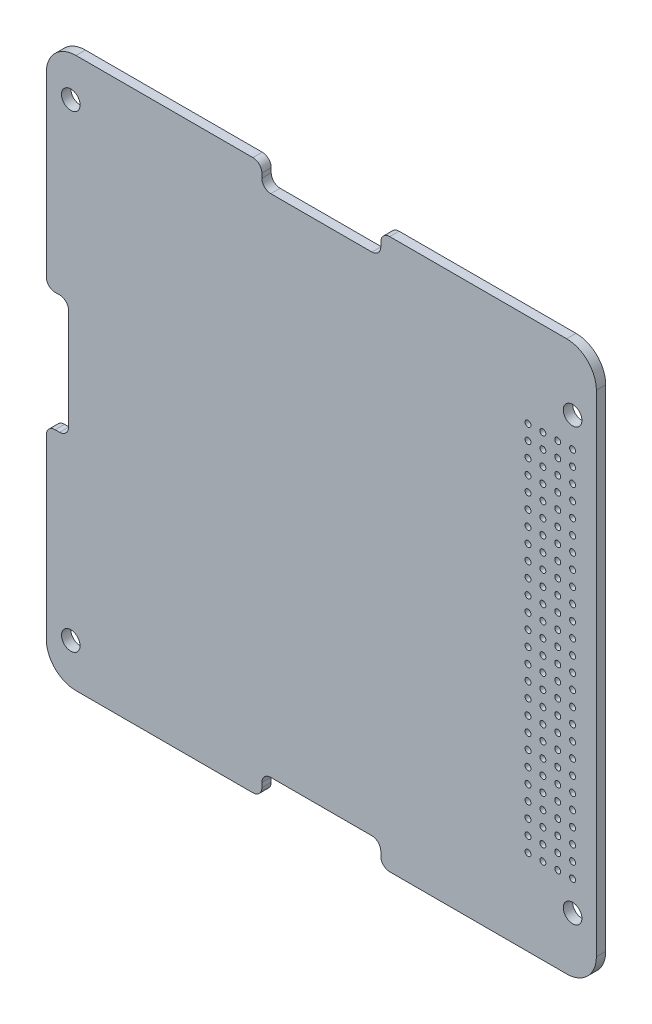
SolidWorks part; units mm, degrees
ref_plane "Front Plane" through (0, 0, 0) normal (0, 0, 1) x (1, 0, 0)
ref_plane "Top Plane" through (0, 0, 0) normal (0, 1, 0) x (1, 0, 0)
ref_plane "Right Plane" through (0, 0, 0) normal (1, 0, 0) x (0, 0, -1)
sketch "Sketch1" plane through (0, 0, 0) normal (0, 0, 1) x (1, 0, 0)
  line L0 (5.08, 0) -> (35.306, 0)
  line L1 (36.83, 1.524) -> (36.83, 2.286)
  line L2 (38.354, 3.81) -> (55.626, 3.81)
  line L3 (57.15, 2.286) -> (57.15, 1.524)
  line L4 (58.674, 0) -> (88.9, 0)
  line L5 (93.98, 5.08) -> (93.98, 88.9)
  line L6 (88.9, 93.98) -> (58.674, 93.98)
  line L7 (57.15, 92.456) -> (57.15, 91.694)
  line L8 (55.626, 90.17) -> (38.354, 90.17)
  line L9 (36.83, 91.694) -> (36.83, 92.456)
  line L10 (35.306, 93.98) -> (5.08, 93.98)
  line L11 (0, 88.9) -> (0, 58.674)
  line L12 (1.524, 57.15) -> (2.286, 57.15)
  line L13 (3.81, 55.626) -> (3.81, 38.354)
  line L14 (2.286, 36.83) -> (1.524, 36.83)
  line L15 (0, 35.306) -> (0, 5.08)
  arc A0 (5.08, 0) -> (0, 5.08) centre (5.08, 5.08) cw
  arc A1 (88.9, 0) -> (93.98, 5.08) centre (88.9, 5.08) ccw
  arc A2 (93.98, 88.9) -> (88.9, 93.98) centre (88.9, 88.9) ccw
  arc A3 (5.08, 93.98) -> (0, 88.9) centre (5.08, 88.9) ccw
  circle A4 centre (4.191, 86.995) radius 1.5875
  circle A5 centre (89.916, 83.185) radius 1.5875
  circle A6 centre (89.916, 9.525) radius 1.5875
  circle A7 centre (4.191, 6.985) radius 1.5875
  circle A8 centre (82.296, 78.105) radius 0.508
  circle A9 centre (84.836, 78.105) radius 0.508
  circle A10 centre (87.376, 78.105) radius 0.508
  circle A11 centre (89.916, 78.105) radius 0.508
  circle A12 centre (84.836, 75.565) radius 0.508
  circle A13 centre (87.376, 75.565) radius 0.508
  circle A14 centre (89.916, 75.565) radius 0.508
  circle A15 centre (84.836, 73.025) radius 0.508
  circle A16 centre (87.376, 73.025) radius 0.508
  circle A17 centre (89.916, 73.025) radius 0.508
  circle A18 centre (84.836, 70.485) radius 0.508
  circle A19 centre (87.376, 70.485) radius 0.508
  circle A20 centre (89.916, 70.485) radius 0.508
  circle A21 centre (84.836, 67.945) radius 0.508
  circle A22 centre (87.376, 67.945) radius 0.508
  circle A23 centre (89.916, 67.945) radius 0.508
  circle A24 centre (84.836, 65.405) radius 0.508
  circle A25 centre (87.376, 65.405) radius 0.508
  circle A26 centre (89.916, 65.405) radius 0.508
  circle A27 centre (84.836, 62.865) radius 0.508
  circle A28 centre (87.376, 62.865) radius 0.508
  circle A29 centre (89.916, 62.865) radius 0.508
  circle A30 centre (84.836, 60.325) radius 0.508
  circle A31 centre (87.376, 60.325) radius 0.508
  circle A32 centre (89.916, 60.325) radius 0.508
  circle A33 centre (84.836, 57.785) radius 0.508
  circle A34 centre (87.376, 57.785) radius 0.508
  circle A35 centre (89.916, 57.785) radius 0.508
  circle A36 centre (84.836, 55.245) radius 0.508
  circle A37 centre (87.376, 55.245) radius 0.508
  circle A38 centre (89.916, 55.245) radius 0.508
  circle A39 centre (84.836, 52.705) radius 0.508
  circle A40 centre (87.376, 52.705) radius 0.508
  circle A41 centre (89.916, 52.705) radius 0.508
  circle A42 centre (84.836, 50.165) radius 0.508
  circle A43 centre (87.376, 50.165) radius 0.508
  circle A44 centre (89.916, 50.165) radius 0.508
  circle A45 centre (84.836, 47.625) radius 0.508
  circle A46 centre (87.376, 47.625) radius 0.508
  circle A47 centre (89.916, 47.625) radius 0.508
  circle A48 centre (84.836, 45.085) radius 0.508
  circle A49 centre (87.376, 45.085) radius 0.508
  circle A50 centre (89.916, 45.085) radius 0.508
  circle A51 centre (84.836, 42.545) radius 0.508
  circle A52 centre (87.376, 42.545) radius 0.508
  circle A53 centre (89.916, 42.545) radius 0.508
  circle A54 centre (84.836, 40.005) radius 0.508
  circle A55 centre (87.376, 40.005) radius 0.508
  circle A56 centre (89.916, 40.005) radius 0.508
  circle A57 centre (84.836, 37.465) radius 0.508
  circle A58 centre (87.376, 37.465) radius 0.508
  circle A59 centre (89.916, 37.465) radius 0.508
  circle A60 centre (84.836, 34.925) radius 0.508
  circle A61 centre (87.376, 34.925) radius 0.508
  circle A62 centre (89.916, 34.925) radius 0.508
  circle A63 centre (84.836, 32.385) radius 0.508
  circle A64 centre (87.376, 32.385) radius 0.508
  circle A65 centre (89.916, 32.385) radius 0.508
  circle A66 centre (84.836, 29.845) radius 0.508
  circle A67 centre (87.376, 29.845) radius 0.508
  circle A68 centre (89.916, 29.845) radius 0.508
  circle A69 centre (84.836, 27.305) radius 0.508
  circle A70 centre (87.376, 27.305) radius 0.508
  circle A71 centre (89.916, 27.305) radius 0.508
  circle A72 centre (84.836, 24.765) radius 0.508
  circle A73 centre (87.376, 24.765) radius 0.508
  circle A74 centre (89.916, 24.765) radius 0.508
  circle A75 centre (84.836, 22.225) radius 0.508
  circle A76 centre (87.376, 22.225) radius 0.508
  circle A77 centre (89.916, 22.225) radius 0.508
  circle A78 centre (84.836, 19.685) radius 0.508
  circle A79 centre (87.376, 19.685) radius 0.508
  circle A80 centre (89.916, 19.685) radius 0.508
  circle A81 centre (84.836, 17.145) radius 0.508
  circle A82 centre (87.376, 17.145) radius 0.508
  circle A83 centre (89.916, 17.145) radius 0.508
  circle A84 centre (84.836, 14.605) radius 0.508
  circle A85 centre (87.376, 14.605) radius 0.508
  circle A86 centre (89.916, 14.605) radius 0.508
  circle A87 centre (82.296, 75.565) radius 0.508
  circle A88 centre (82.296, 73.025) radius 0.508
  circle A89 centre (82.296, 70.485) radius 0.508
  circle A90 centre (82.296, 67.945) radius 0.508
  circle A91 centre (82.296, 65.405) radius 0.508
  circle A92 centre (82.296, 62.865) radius 0.508
  circle A93 centre (82.296, 60.325) radius 0.508
  circle A94 centre (82.296, 57.785) radius 0.508
  circle A95 centre (82.296, 55.245) radius 0.508
  circle A96 centre (82.296, 52.705) radius 0.508
  circle A97 centre (82.296, 50.165) radius 0.508
  circle A98 centre (82.296, 47.625) radius 0.508
  circle A99 centre (82.296, 45.085) radius 0.508
  circle A100 centre (82.296, 42.545) radius 0.508
  circle A101 centre (82.296, 40.005) radius 0.508
  circle A102 centre (82.296, 37.465) radius 0.508
  circle A103 centre (82.296, 34.925) radius 0.508
  circle A104 centre (82.296, 32.385) radius 0.508
  circle A105 centre (82.296, 29.845) radius 0.508
  circle A106 centre (82.296, 27.305) radius 0.508
  circle A107 centre (82.296, 24.765) radius 0.508
  circle A108 centre (82.296, 22.225) radius 0.508
  circle A109 centre (82.296, 19.685) radius 0.508
  circle A110 centre (82.296, 17.145) radius 0.508
  circle A111 centre (82.296, 14.605) radius 0.508
  arc A112 (58.674, 93.98) -> (57.15, 92.456) centre (58.674, 92.456) ccw
  arc A113 (57.15, 91.694) -> (55.626, 90.17) centre (55.626, 91.694) cw
  arc A114 (38.354, 90.17) -> (36.83, 91.694) centre (38.354, 91.694) cw
  arc A115 (36.83, 92.456) -> (35.306, 93.98) centre (35.306, 92.456) ccw
  arc A116 (0, 58.674) -> (1.524, 57.15) centre (1.524, 58.674) ccw
  arc A117 (2.286, 57.15) -> (3.81, 55.626) centre (2.286, 55.626) cw
  arc A118 (3.81, 38.354) -> (2.286, 36.83) centre (2.286, 38.354) cw
  arc A119 (1.524, 36.83) -> (0, 35.306) centre (1.524, 35.306) ccw
  arc A120 (35.306, 0) -> (36.83, 1.524) centre (35.306, 1.524) ccw
  arc A121 (36.83, 2.286) -> (38.354, 3.81) centre (38.354, 2.286) cw
  arc A122 (55.626, 3.81) -> (57.15, 2.286) centre (55.626, 2.286) cw
  arc A123 (57.15, 1.524) -> (58.674, 0) centre (58.674, 1.524) ccw
  point P19 (0, 0)
  point P273 (36.83, 0)
  dimension "D7" = 5.08
  dimension "D8" = 3.175
  dimension "D9" = 1.016
  dimension "D22" = 1.524
  dimension "D1" = 93.98
  dimension "D2" = 93.98
  dimension "D3" = 36.83
  dimension "D4" = 3.81
  dimension "D5" = 3.81
  dimension "D6" = 3.81
  dimension "D10" = 4
  dimension "D11" = 26
  dimension "D12" = 85.725
  dimension "D13" = 85.725
  dimension "D14" = 80.01
  dimension "D15" = 73.66
  dimension "D16" = 3.81
  dimension "D17" = 5.08
  dimension "D18" = 6.985
  dimension "D19" = 6.985
  dimension "D20" = 4.191
  dimension "D21" = 4.064
extrude "Boss-Extrude1" add sketch "Sketch1" along normal blind 1.6
